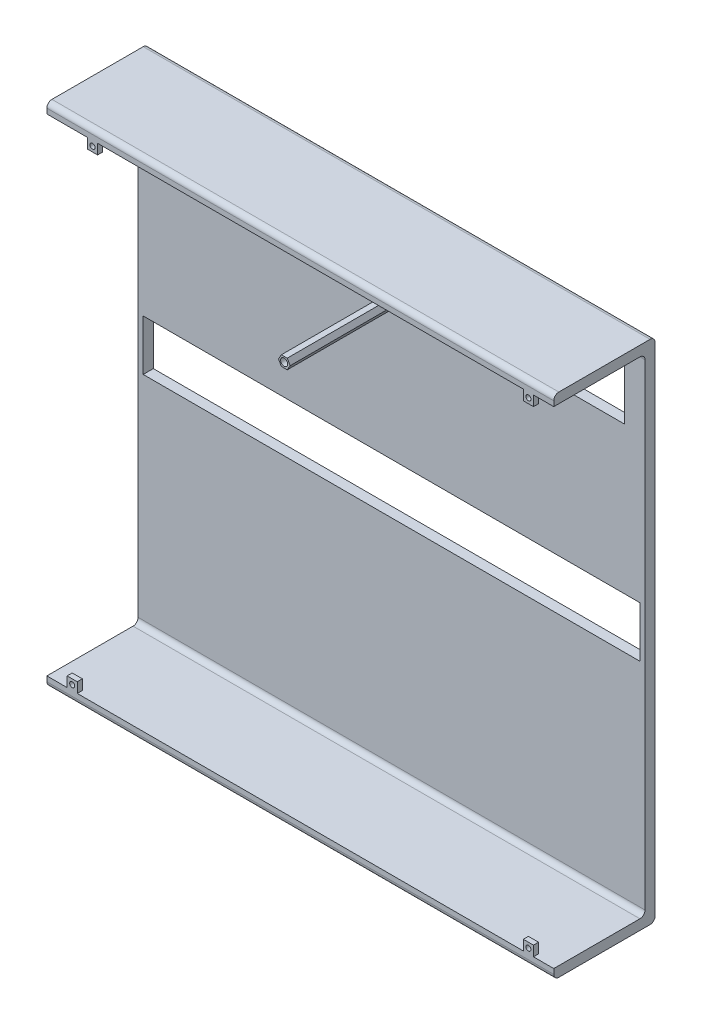
SolidWorks part; units mm, degrees
ref_plane "Alzado" through (0, 0, 0) normal (0, 0, 1) x (1, 0, 0)
ref_plane "Planta" through (0, 0, 0) normal (0, 1, 0) x (1, 0, 0)
ref_plane "Vista lateral" through (0, 0, 0) normal (1, 0, 0) x (0, 0, -1)
sketch "Croquis1" plane through (0, 0, 0) normal (0, 0, 1) x (1, 0, 0)
  line L2 (-25, -25) -> (25, -25)
  line L3 (-25, -25) -> (-25, 25)
  line L4 (-25, 25) -> (25, 25)
  line L5 (25, -25) -> (25, 25)
  line L6 (0, 25) -> (0, -25) construction
  line L7 (-25, 0) -> (25, 0) construction
  point P0 (0, 0)
  dimension "D1" = 50
extrude "Saliente-Extruir1" add sketch "Croquis1" along normal blind 10
sketch "Croquis2" plane through (0, 0, 0) normal (0, 0, -1) x (-1, 0, 0)
  line L1 (-24.5, 2.5) -> (24.5, 2.5)
  line L2 (-24.5, 2.5) -> (-24.5, -2.5)
  line L3 (-24.5, -2.5) -> (24.5, -2.5)
  line L4 (24.5, 2.5) -> (24.5, -2.5)
  line L5 (0, -2.5) -> (0, 2.5) construction
  line L6 (-24.5, 0) -> (24.5, 0) construction
  point P0 (0, 0)
  dimension "D1" = 5
  dimension "D2" = 49
extrude "Cortar-Extruir2" cut sketch "Croquis2" against normal blind 6
sketch "Croquis3" plane through (0, 0, 0) normal (0, 0, -1) x (-1, 0, 0)
  line L1 (-23, 22) -> (-13, 22)
  line L2 (-23, 22) -> (-23, 17)
  line L3 (-23, 17) -> (-13, 17)
  line L4 (-13, 22) -> (-13, 17)
  line L7 (-25, 25) -> (25, 25) construction
  line L8 (-25, -25) -> (-25, 25) construction
  dimension "D1" = 10
  dimension "D2" = 5
  dimension "D3" = 3
  dimension "D4" = 2
extrude "Cortar-Extruir3" cut sketch "Croquis3" against normal blind 6 contours L2 L1 L4 L3
sketch "Croquis4" plane through (0, 0, 0) normal (0, 0, -1) x (-1, 0, 0)
  line L0 (25, 25) -> (25, -25) construction
  line L3 (-25, 25) -> (25, 25) construction
  circle A0 centre (23, 21) radius 1
  point P6 (22.0414, 25)
  point P7 (22.355, 25)
  dimension "D1" = 2
  dimension "D2" = 2
  dimension "D3" = 4
extrude "Cortar-Extruir4" cut sketch "Croquis4" against normal blind 6
sketch "Croquis5" plane through (25, 0, 0) normal (1, 0, 0) x (0, 0, -1)
  line L0 (-10, 25) -> (0, 25) construction
  line L1 (-10, 24) -> (-1, 24)
  line L2 (-10, 24) -> (-10, -24)
  line L3 (-10, -24) -> (-1, -24)
  line L4 (-1, 24) -> (-1, -24)
  line L5 (-10, -25) -> (-10, 25) construction
  dimension "D1" = 1
  dimension "D2" = 0
  dimension "D3" = 9
  dimension "D4" = 48
extrude "Cortar-Extruir5" cut sketch "Croquis5" against normal blind 50
sketch "Croquis6" plane through (0, 24, 0) normal (0, -1, 0) x (1, 0, 0)
  line L0 (-25, 10) -> (-25, 0) construction
  line L1 (-21, 10) -> (-20, 10)
  line L2 (-21, 10) -> (-21, 9.5)
  line L3 (-21, 9.5) -> (-20, 9.5)
  line L4 (-20, 10) -> (-20, 9.5)
  line L5 (-25, 10) -> (25, 10) construction
  dimension "D1" = 0.5
  dimension "D2" = 1
  dimension "D3" = 4
  dimension "D4" = 0
extrude "Saliente-Extruir2" add sketch "Croquis6" along normal blind 1
sketch "Croquis7" plane through (0, 24, 0) normal (0, -1, 0) x (1, 0, 0)
  line L0 (25, 10) -> (25, 0) construction
  line L1 (22, 10) -> (23, 10)
  line L2 (22, 10) -> (22, 9.5)
  line L3 (22, 9.5) -> (23, 9.5)
  line L4 (23, 10) -> (23, 9.5)
  line L5 (-25, 10) -> (25, 10) construction
  dimension "D1" = 1
  dimension "D2" = 0.5
  dimension "D3" = 2
  dimension "D4" = 0
extrude "Saliente-Extruir3" add sketch "Croquis7" along normal blind 1
sketch "Croquis9" plane through (0, -24, 0) normal (0, 1, 0) x (1, 0, 0)
  line L0 (25, -10) -> (-25, -10) construction
  line L1 (-23, -9.5) -> (-22, -9.5)
  line L2 (-23, -9.5) -> (-23, -10)
  line L3 (-23, -10) -> (-22, -10)
  line L4 (-22, -9.5) -> (-22, -10)
  line L5 (-25, -10) -> (-25, 0) construction
  dimension "D1" = 1
  dimension "D2" = 0.5
  dimension "D3" = 0
  dimension "D4" = 2
extrude "Saliente-Extruir4" add sketch "Croquis9" along normal blind 1
sketch "Croquis10" plane through (0, -24, 0) normal (0, 1, 0) x (1, 0, 0)
  line L0 (25, -10) -> (-25, -10) construction
  line L1 (23, -10) -> (22, -10)
  line L2 (23, -10) -> (23, -9.5)
  line L3 (23, -9.5) -> (22, -9.5)
  line L4 (22, -10) -> (22, -9.5)
  line L5 (25, -10) -> (25, 0) construction
  point P8 (23, -9.75)
  dimension "D1" = 1
  dimension "D2" = 0.5
  dimension "D3" = 0
  dimension "D4" = 2
extrude "Saliente-Extruir5" add sketch "Croquis10" along normal blind 1
sketch "Croquis11" plane through (0, 0, 1) normal (0, 0, 1) x (1, 0, 0)
  line L0 (-25, 24) -> (25, 24) construction
  line L1 (0, 15.5) -> (-0.2887, 16)
  line L2 (-0.2887, 16) -> (-0.866, 16)
  line L3 (-0.866, 16) -> (-1.1547, 15.5)
  line L4 (-1.1547, 15.5) -> (-0.866, 15)
  line L5 (-0.866, 15) -> (-0.2887, 15)
  line L6 (-0.2887, 15) -> (0, 15.5)
  line L7 (25, -25) -> (25, 25) construction
  circle A0 centre (-0.5774, 15.5) radius 0.5 construction
  dimension "D1" = 1
  dimension "D2" = 8
  dimension "D3" = 25
extrude "Saliente-Extruir6" add sketch "Croquis11" along normal blind 10
sketch "Croquis12" plane through (0, 0, 11) normal (0, 0, 1) x (1, 0, 0)
  line L1 (-0.2887, 16) -> (-0.866, 16) construction
  circle A0 centre (-0.6, 15.5) radius 0.35
  point P2 (0, 0)
  point P3 (0, 0)
  point P5 (0, 0)
  dimension "D1" = 0.7
  dimension "D2" = 0.5
  dimension "D3" = 0.6
extrude "Cortar-Extruir6" cut sketch "Croquis12" against normal blind 9
sketch "Croquis13" plane through (0, 0, 10) normal (0, 0, 1) x (1, 0, 0)
  line L0 (-20, 23) -> (-21, 23) construction
  line L1 (-21, 23) -> (-21, 24) construction
  circle A0 centre (-20.5, 23.5) radius 0.25
  dimension "D1" = 0.5
  dimension "D2" = 0.5
  dimension "D3" = 0.5
extrude "Cortar-Extruir7" cut sketch "Croquis13" against normal blind 2
sketch "Croquis14" plane through (0, 0, 10) normal (0, 0, 1) x (1, 0, 0)
  line L0 (23, 23) -> (23, 24) construction
  line L1 (23, 23) -> (22, 23) construction
  circle A0 centre (22.5, 23.5) radius 0.25
  dimension "D1" = 0.5
  dimension "D2" = 0.5
  dimension "D3" = 0.5
extrude "Cortar-Extruir8" cut sketch "Croquis14" against normal blind 2
sketch "Croquis15" plane through (0, 0, 10) normal (0, 0, 1) x (1, 0, 0)
  line L0 (-23, -23) -> (-23, -24) construction
  line L1 (-23, -23) -> (-22, -23) construction
  circle A0 centre (-22.5, -23.5) radius 0.25
  point P6 (-22.6206, -23.1768)
  dimension "D1" = 0.5
  dimension "D2" = 0.5
  dimension "D3" = 0.5
extrude "Cortar-Extruir9" cut sketch "Croquis15" against normal blind 2
sketch "Croquis16" plane through (0, 0, 10) normal (0, 0, 1) x (1, 0, 0)
  line L0 (22, -23) -> (22, -24) construction
  line L1 (22, -23) -> (23, -23) construction
  circle A0 centre (22.5, -23.5) radius 0.25
  dimension "D1" = 0.5
  dimension "D2" = 0.5
  dimension "D3" = 0.5
extrude "Cortar-Extruir10" cut sketch "Croquis16" against normal blind 2
fillet "Redondeo5" radius 0.5 1 edges at (0, 25, 0)
fillet "Redondeo6" radius 0.5 1 edges at (0, -25, 0)
fillet "Redondeo7" radius 0.5 1 edges at (0, 24, 1)
fillet "Redondeo8" radius 0.5 1 edges at (0, -24, 1)
fillet "Redondeo9" radius 0.5 1 edges at (0, 25, 10)
fillet "Redondeo10" radius 0.5 1 edges at (0, -25, 10)
